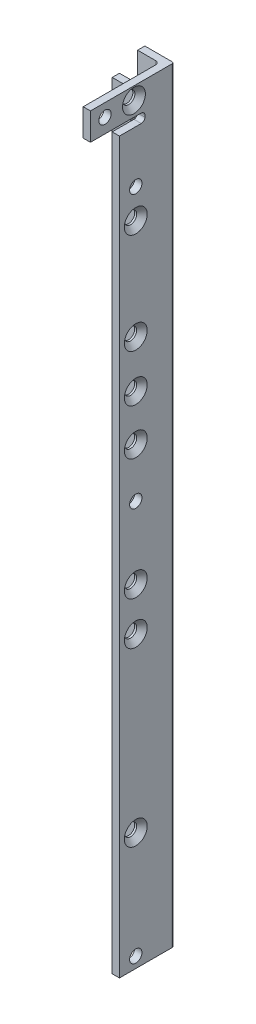
SolidWorks part; units mm, degrees
material "6061-T6 (SS)"
ref_plane "Front Plane" through (0, 0, 0) normal (0, 0, 1) x (1, 0, 0)
ref_plane "Top Plane" through (0, 0, 0) normal (0, 1, 0) x (1, 0, 0)
ref_plane "Right Plane" through (0, 0, 0) normal (1, 0, 0) x (0, 0, -1)
sketch "Sketch1" plane through (0, 0, 0) normal (0, 1, 0) x (1, 0, 0)
  line L1 (0, 0) -> (15, 0)
  line L2 (0, 0) -> (0, 15)
  line L3 (0, 15) -> (15, 15)
  line L4 (15, 0) -> (15, 15)
  line L5 (0, 0) -> (13, 0)
  line L6 (0, 0) -> (0, 13)
  line L7 (0, 13) -> (13, 13)
  line L8 (13, 0) -> (13, 13)
  dimension "D1" = 15
  dimension "D2" = 15
  dimension "D3" = 2
  dimension "D4" = 2
extrude "Boss-Extrude1" add sketch "Sketch1" along normal blind 211 contours L8 L1 L4 L3 L2 L7
sketch "Sketch2" plane through (15, 0, 0) normal (1, 0, 0) x (0, 0, -1)
  line L0 (4.5, 211) -> (31.285, 211)
  line L1 (0, 211) -> (15, 211) construction
  line L2 (0, 211) -> (0, 0) construction
  line L3 (-137.0416, 210.9757) -> (-37.0416, 210.9757)
  circle A0 centre (4.5, 32.4507) radius 1.6
  circle A1 centre (4.5, 79.8607) radius 1.6
  circle A2 centre (4.5, 103.4607) radius 1.6
  circle A3 centre (4.5, 125.1207) radius 1.6
  circle A4 centre (4.5, 137.8117) radius 1.6
  circle A5 centre (4.5, 150.8117) radius 1.6
  circle A6 centre (4.5, 178.5483) radius 1.6
  circle A7 centre (-126.5416, 43.1674) radius 1.6
  circle A8 centre (-126.5416, 79.8364) radius 1.55
  circle A9 centre (-126.5416, 103.4364) radius 1.55
  circle A10 centre (-126.5416, 125.0964) radius 1.6
  circle A11 centre (-126.5416, 137.7874) radius 1.55
  circle A12 centre (-126.5416, 150.7874) radius 1.55
  circle A13 centre (-126.5416, 178.524) radius 1.55
  dimension "D1" = 32.4517
  dimension "D2" = 27.7366
  dimension "D3" = 13
  dimension "D4" = 12.691
  dimension "D5" = 21.66
  dimension "D6" = 23.6
  dimension "D7" = 26.785
  dimension "D8" = 4.5
  dimension "D9" = 47.41
  dimension "D10" = 27.7366
  dimension "D11" = 13
  dimension "D12" = 12.691
  dimension "D13" = 21.66
  dimension "D14" = 23.6
  dimension "D15" = 36.669
  dimension "D16" = 32.4517
hole_wizard "CSK for M3 Flat Head Machine Screw1" positions "Sketch3" profile "Sketch4" countersink size "M3" standard "ANSI Metric" end condition through all
sketch "Sketch3" plane through (15, 0, 0) normal (1, 0, 0) x (0, 0, -1)
  line L0 (9, 87.589) -> (0, 87.589) construction
  point P0 (4.5, 178.5483)
  point P3 (4.5, 150.8117)
  point P6 (4.5, 137.8117)
  point P9 (4.5, 125.1207)
  point P12 (4.5, 91.719)
  point P15 (4.5, 79.8607)
  point P18 (4.5, 32.4507)
  dimension "D1" = 4.13
sketch "Sketch4" plane through (15, 178.5483, -4.5) normal (0, 1, 0) x (0, 0, -1)
  line L0 (0, 0) -> (0, 15)
  line L1 (0, 15) -> (1.7, 15)
  line L2 (1.7, 15) -> (1.7, 1.45)
  line L3 (1.7, 1.45) -> (3.15, 0)
  line L5 (3.15, 0) -> (0, 0)
  line L6 (-1.7, 1.45) -> (-3.15, 0) construction
  line L11 (0, -6.35) -> (0, 107.95) construction
  dimension "Thru Hole Dia." = 3.4
  dimension "Thru Hole Depth" = 15
  dimension "Near C'Sink Dia." = 6.3
  dimension "Near C'Sink Angle" = 90
sketch "Sketch5" plane through (0, 0, -15) normal (0, 0, -1) x (-1, 0, 0)
  line L0 (0, 211) -> (0, 0) construction
  line L1 (0, 211) -> (-7, 211)
  line L2 (0, 211) -> (0, 201)
  line L3 (0, 201) -> (-7, 201)
  line L4 (-7, 211) -> (-7, 201)
  line L5 (-15, 211) -> (-15, 0) construction
  line L6 (0, 211) -> (-15, 211) construction
  dimension "D1" = 8
  dimension "D2" = 0
  dimension "D3" = 10
extrude "Cut-Extrude1" cut sketch "Sketch5" against normal through all
sketch "Sketch6" plane through (15, 0, 0) normal (1, 0, 0) x (0, 0, -1)
  line L0 (0, 211) -> (0, 0) construction
  line L1 (0, 201) -> (7, 201)
  line L2 (0, 201) -> (0, 203.5)
  line L3 (0, 203.5) -> (7, 203.5)
  line L4 (7, 201) -> (7, 203.5)
  line L5 (15, 211) -> (15, 0) construction
  dimension "D1" = 2.5
  dimension "D2" = 8
extrude "Cut-Extrude2" cut sketch "Sketch6" against normal through all
sketch "Sketch7" plane through (15, 0, 0) normal (1, 0, 0) x (0, 0, -1)
  line L0 (0, 211) -> (0, 203.5) construction
  line L2 (0, 211) -> (15, 211) construction
  circle A0 centre (4, 207.5) radius 1.744
  dimension "D1" = 4
  dimension "D2" = 3.5
hole_wizard "CSK for M3 Flat Head Machine Screw2" positions "Sketch8" profile "Sketch9" countersink size "M3" standard "ANSI Metric" end condition through all
sketch "Sketch8" plane through (15, 0, 0) normal (1, 0, 0) x (0, 0, -1)
  point P0 (4, 207.5)
sketch "Sketch9" plane through (15, 207.5, -4) normal (0, 1, 0) x (0, 0, -1)
  line L0 (0, 0) -> (0, 15)
  line L1 (0, 15) -> (1.7, 15)
  line L2 (1.7, 15) -> (1.7, 1.45)
  line L3 (1.7, 1.45) -> (3.15, 0)
  line L5 (3.15, 0) -> (0, 0)
  line L6 (-1.7, 1.45) -> (-3.15, 0) construction
  line L11 (0, -6.35) -> (0, 107.95) construction
  dimension "Thru Hole Dia." = 3.4
  dimension "Thru Hole Depth" = 15
  dimension "Near C'Sink Dia." = 6.3
  dimension "Near C'Sink Angle" = 90
sketch "Sketch10" plane through (0, 0, -15) normal (0, 0, -1) x (-1, 0, 0)
  line L0 (0, 201) -> (0, 0) construction
  line L1 (0, 0) -> (-15, 0) construction
  circle A0 centre (-4, 3.5) radius 2.1354
  dimension "D1" = 4
  dimension "D2" = 3.5
hole_wizard "CSK for M3 Flat Head Machine Screw3" positions "Sketch11" profile "Sketch12" countersink size "M3" standard "ANSI Metric" end condition through all
sketch "Sketch11" plane through (0, 0, -15) normal (0, 0, -1) x (-1, 0, 0)
  line L0 (-7, 211) -> (-15, 211) construction
  line L1 (0, 201) -> (0, 0) construction
  circle A0 centre (-4.5, 195) radius 3.4276
  point P0 (-4, 3.5)
  point P3 (-4.5, 195)
  dimension "D1" = 16
  dimension "D2" = 4.5
sketch "Sketch12" plane through (4, 3.5, -15) normal (1, 0, 0) x (0, 1, 0)
  line L0 (0, 0) -> (0, 15)
  line L1 (0, 15) -> (1.7, 15)
  line L2 (1.7, 15) -> (1.7, 1.45)
  line L3 (1.7, 1.45) -> (3.15, 0)
  line L5 (3.15, 0) -> (0, 0)
  line L6 (-1.7, 1.45) -> (-3.15, 0) construction
  line L11 (0, -6.35) -> (0, 107.95) construction
  dimension "Thru Hole Dia." = 3.4
  dimension "Thru Hole Depth" = 15
  dimension "Near C'Sink Dia." = 6.3
  dimension "Near C'Sink Angle" = 90
fillet "Fillet1" radius 0.5 1 edges at (15, 105.5, -15)
fillet "Fillet2" radius 1 4 edges at (14, 201, -7) (14, 203.5, -7) (13, 105.5, -13) (7, 201, -14)
sketch "Sketch13" plane through (15, 0, 0) normal (1, 0, 0) x (0, 0, -1)
  line L0 (0, 0) -> (14.5, 0) construction
  circle A0 centre (4.5, 186.68) radius 1.7
  circle A1 centre (4.5, 111.59) radius 1.7
  circle A2 centre (4.5, 3) radius 1.7
  circle A3 centre (4.5, 32.4507) radius 1.7 construction
  circle A4 centre (4.5, 32.4507) radius 1.7
  dimension "D1" = 3
  dimension "D2" = 111.59
  dimension "D3" = 186.68
extrude "Cut-Extrude3" cut sketch "Sketch13" against normal blind 10
sketch "Sketch14" plane through (0, 0, -15) normal (0, 0, -1) x (-1, 0, 0)
  line L2 (0, 0) -> (-14.5, 0) construction
  circle A2 centre (-4.5, 186.68) radius 1.7
  circle A3 centre (-4.5, 111.59) radius 1.7
  circle A4 centre (-4.5, 10) radius 1.7
  circle A5 centre (-4.5, 195) radius 1.7 construction
  circle A6 centre (-4.5, 195) radius 1.7
  dimension "D1" = 10
  dimension "D2" = 111.59
  dimension "D3" = 186.68
extrude "Cut-Extrude4" cut sketch "Sketch14" against normal blind 10
sketch "Sketch15" plane through (0, 0, 0) normal (0, 0, 1) x (1, 0, 0)
  line L1 (13, 211) -> (15, 211)
  line L2 (13, 211) -> (13, 203.5)
  line L3 (13, 203.5) -> (15, 203.5)
  line L4 (15, 211) -> (15, 203.5)
  dimension "D1" = 7.5
  dimension "D2" = 2
extrude "Boss-Extrude2" add sketch "Sketch15" along normal blind 8
sketch "Sketch16" plane through (13, 0, 0) normal (-1, 0, 0) x (0, 0, 1)
  line L4 (8, 211) -> (-12, 211) construction
  line L5 (8, 211) -> (8, 203.5) construction
  circle A0 centre (4, 207.5) radius 1.7
  point P2 (0, 0)
  point P8 (4.1699, 207.4753)
  dimension "D1" = 3.5
  dimension "D2" = 4
extrude "Cut-Extrude5" cut sketch "Sketch16" against normal blind 8
